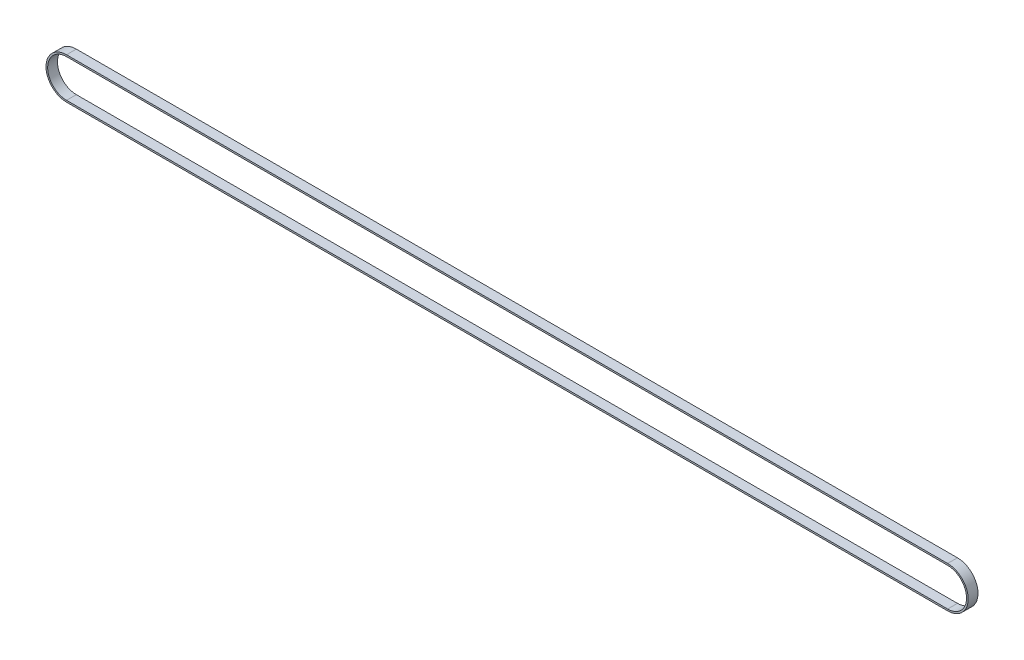
SolidWorks part; units mm, degrees
ref_plane "Plano frontal" through (0, 0, 0) normal (0, 0, 1) x (1, 0, 0)
ref_plane "Plano superior" through (0, 0, 0) normal (0, 1, 0) x (1, 0, 0)
ref_plane "Plano direito" through (0, 0, 0) normal (1, 0, 0) x (0, 0, -1)
sketch "Esboço1" plane through (0, 0, 0) normal (0, 0, 1) x (1, 0, 0)
  line L0 (-186.5, 0) -> (186.5, 0) construction
  line L1 (-186.5, 8) -> (186.5, 8)
  line L2 (-186.5, -8) -> (186.5, -8)
  line L3 (-186.5, 8.7) -> (186.5, 8.7)
  line L4 (-186.5, -8.7) -> (186.5, -8.7)
  arc A0 (-186.5, 8) -> (-186.5, -8) centre (-186.5, 0) ccw
  arc A1 (186.5, -8) -> (186.5, 8) centre (186.5, 0) ccw
  arc A2 (186.5, -8.7) -> (186.5, 8.7) centre (186.5, 0) ccw
  arc A3 (-186.5, 8.7) -> (-186.5, -8.7) centre (-186.5, 0) ccw
  point P2 (0, 0)
extrude "Ressalto-extrusão1" add sketch "Esboço1" along normal blind 4.15
